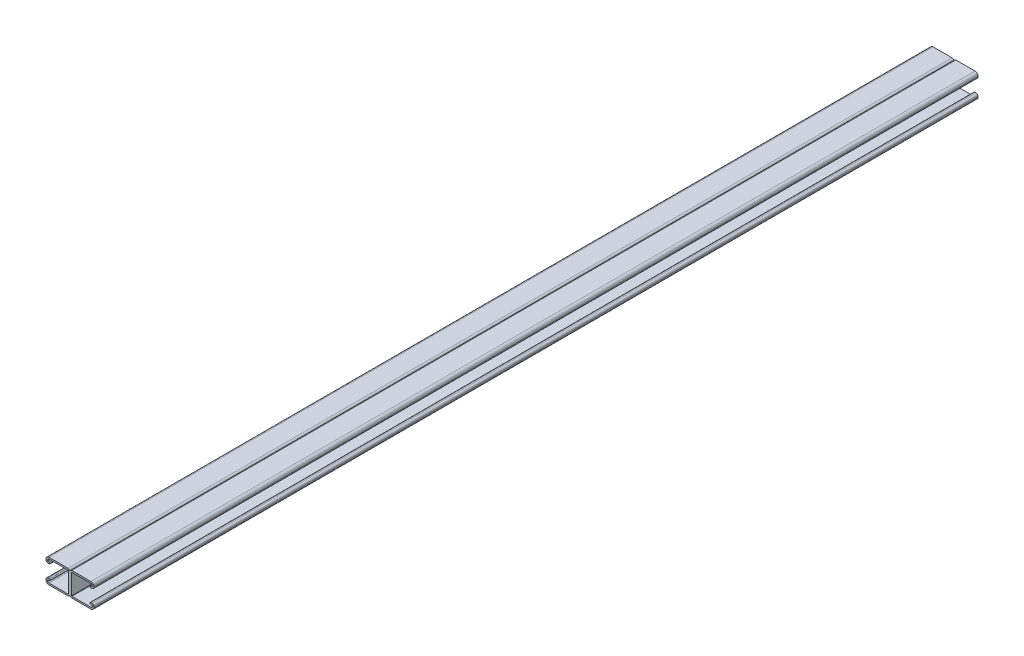
SolidWorks part; units mm, degrees
ref_plane "Front Plane" through (0, 0, 0) normal (0, 0, 1) x (1, 0, 0)
ref_plane "Top Plane" through (0, 0, 0) normal (0, 1, 0) x (1, 0, 0)
ref_plane "Right Plane" through (0, 0, 0) normal (1, 0, 0) x (0, 0, -1)
sketch "Sketch1" plane through (0, 0, 0) normal (0, 0, 1) x (1, 0, 0)
  line L0 (0, 0) -> (-41.275, 0) construction
  line L3 (-41.275, 20.6375) -> (0, 20.6375) construction
  line L4 (-41.275, 20.6375) -> (-41.275, -20.6375) construction
  line L5 (-41.275, -20.6375) -> (0, -20.6375) construction
  line L6 (0, 20.6375) -> (0, -20.6375) construction
  line L7 (-36.2267, 20.6375) -> (-3.4607, 20.6375)
  line L8 (0, 17.1767) -> (0, -17.1767)
  line L9 (-2.794, -17.1767) -> (-2.794, 17.1767)
  line L10 (-3.4608, 17.8435) -> (-36.2267, 17.8435)
  line L11 (-41.275, 15.5892) -> (-41.275, 14.5732)
  line L12 (-37.8142, 11.1125) -> (-35.5346, 11.1125)
  line L14 (-35.5346, 13.9065) -> (-37.8142, 13.9065)
  line L15 (-38.481, 14.5732) -> (-38.481, 15.5892)
  line L16 (-38.481, -14.5733) -> (-38.481, -15.5893)
  line L17 (-35.5346, -13.9065) -> (-37.8142, -13.9065)
  line L18 (-37.8142, -11.1125) -> (-35.5346, -11.1125)
  line L19 (-41.275, -15.5893) -> (-41.275, -14.5733)
  line L20 (-3.4607, -17.8435) -> (-36.2267, -17.8435)
  line L21 (-36.2267, -20.6375) -> (-3.4607, -20.6375)
  line L22 (-2.794, -20.6375) -> (-2.794, 20.6375) construction
  arc A1 (0, 17.1767) -> (-3.4607, 20.6375) centre (-3.4607, 17.1767) ccw
  arc A2 (-2.794, 17.1767) -> (-3.4608, 17.8435) centre (-3.4607, 17.1767) ccw
  arc A4 (-36.2267, 20.6375) -> (-41.275, 15.5892) centre (-36.2267, 15.5892) ccw
  arc A5 (-41.275, 14.5732) -> (-37.8142, 11.1125) centre (-37.8142, 14.5732) ccw
  arc A6 (-35.5346, 11.1125) -> (-35.5346, 13.9065) centre (-35.5346, 12.5095) ccw
  arc A7 (-37.8142, 13.9065) -> (-38.481, 14.5732) centre (-37.8142, 14.5732) cw
  arc A8 (-38.481, 15.5892) -> (-36.2267, 17.8435) centre (-36.2267, 15.5892) cw
  arc A9 (-38.481, -15.5893) -> (-36.2267, -17.8435) centre (-36.2267, -15.5893) ccw
  arc A10 (-37.8142, -13.9065) -> (-38.481, -14.5733) centre (-37.8142, -14.5733) ccw
  arc A11 (-35.5346, -11.1125) -> (-35.5346, -13.9065) centre (-35.5346, -12.5095) cw
  arc A12 (-41.275, -14.5733) -> (-37.8142, -11.1125) centre (-37.8142, -14.5733) cw
  arc A13 (-36.2267, -20.6375) -> (-41.275, -15.5893) centre (-36.2267, -15.5893) cw
  arc A14 (-2.794, -17.1767) -> (-3.4607, -17.8435) centre (-3.4607, -17.1767) cw
  arc A15 (0, -17.1767) -> (-3.4607, -20.6375) centre (-3.4607, -17.1767) cw
  point P24 (0, 20.6375)
  point P65 (-2.794, 0)
  dimension "D1" = 3.4608
  dimension "D2" = 5.0482
  dimension "D3" = 3.4608
  dimension "Ht." = 41.275
  dimension "Wd." = 41.275
  dimension "Thk." = 2.794
  dimension "D4" = 9.525
  dimension "D5" = 7.1374
extrude "Boss-Extrude1" add sketch "Sketch1" against normal blind 1524
sketch "Sketch3" plane through (0, 0, 0) normal (1, 0, 0) x (0, 0, -1)
  line L0 (0, 0) -> (1524, 0) construction
  point P2 (101.6, 0)
  point P3 (1422.4, 0)
  dimension "D1" = 101.6
  dimension "D2" = 101.6
  dimension "D3" = 1524
mirror "Mirror1" about plane through (0, 17.1767, -1524) normal (1, 0, 0) of bodies 114
combine bodies "Combine1" operation type add bodies to combine 117 114
equation "\"D3@Sketch3\" = \"Lg.@Boss-Extrude1\""
